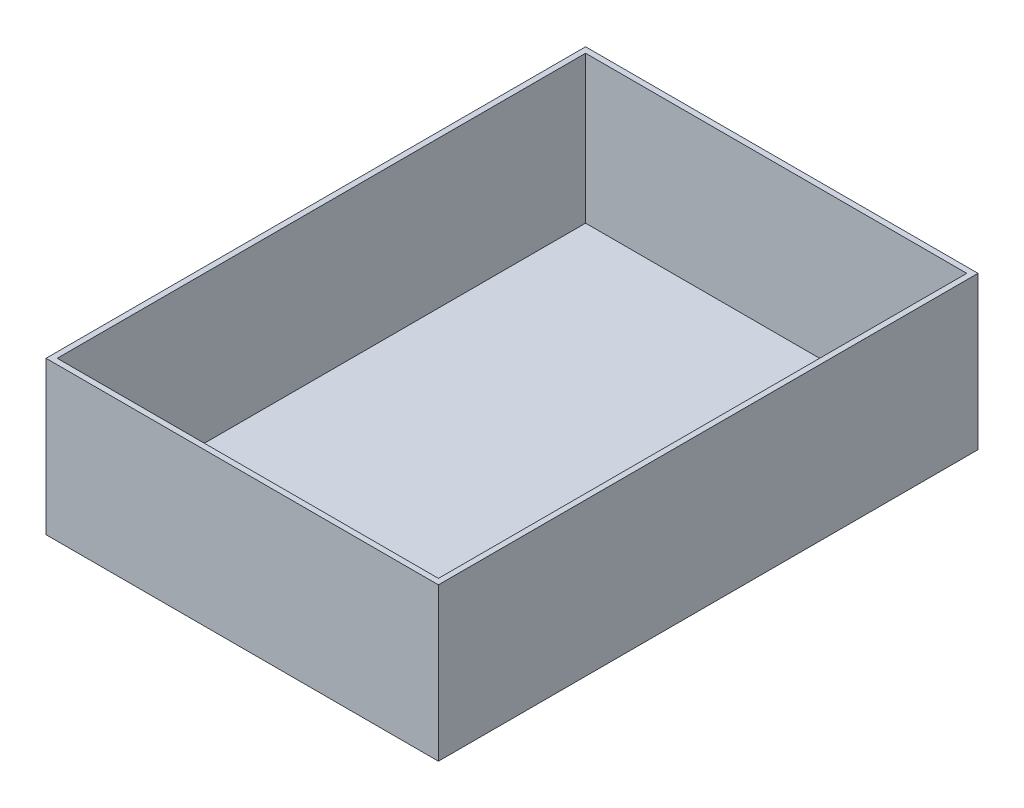
SolidWorks part; units mm, degrees
ref_plane "前视基准面" through (0, 0, 0) normal (0, 0, 1) x (1, 0, 0)
ref_plane "上视基准面" through (0, 0, 0) normal (0, 1, 0) x (1, 0, 0)
ref_plane "右视基准面" through (0, 0, 0) normal (1, 0, 0) x (0, 0, -1)
sketch "草图1" plane through (0, 0, 0) normal (0, 1, 0) x (1, 0, 0)
  line L1 (-28, -38.5) -> (28, -38.5)
  line L2 (-28, -38.5) -> (-28, 38.5)
  line L3 (-28, 38.5) -> (28, 38.5)
  line L4 (28, -38.5) -> (28, 38.5)
  line L5 (-28, -38.5) -> (28, 38.5) construction
  line L6 (-28, 38.5) -> (28, -38.5) construction
  point P0 (0, 0)
  dimension "D1" = 56
  dimension "D2" = 77
extrude "凸台-拉伸1" add sketch "草图1" along normal blind 21.8
shell "抽壳1" thickness 0.8
